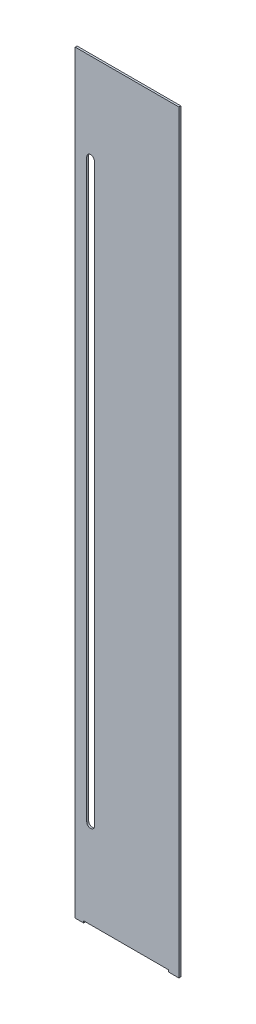
SolidWorks part; units mm, degrees
ref_plane "Front Plane" through (0, 0, 0) normal (0, 0, 1) x (1, 0, 0)
ref_plane "Top Plane" through (0, 0, 0) normal (0, 1, 0) x (1, 0, 0)
ref_plane "Right Plane" through (0, 0, 0) normal (1, 0, 0) x (0, 0, -1)
sketch "Sketch1" plane through (0, 0, 0) normal (0, 0, 1) x (1, 0, 0)
  line L1 (-135, 982.5) -> (135, 982.5)
  line L2 (-135, 982.5) -> (-135, -982.5)
  line L3 (-135, -982.5) -> (135, -982.5)
  line L4 (135, 982.5) -> (135, -982.5)
  line L5 (-135, 982.5) -> (135, -982.5) construction
  line L6 (-135, -982.5) -> (135, 982.5) construction
  point P0 (0, 0)
  dimension "D1" = 270
  dimension "D2" = 1965
extrude "Main plate extrude" add sketch "Sketch1" along normal blind 5
sketch "Sketch2" plane through (0, 0, 5) normal (0, 0, 1) x (1, 0, 0)
  line L0 (-135, -982.5) -> (135, -982.5) construction
  line L1 (-113, -982.5) -> (108, -982.5)
  line L2 (-113, -982.5) -> (-113, -977.5)
  line L3 (-113, -977.5) -> (108, -977.5)
  line L4 (108, -982.5) -> (108, -977.5)
  line L5 (-135, 982.5) -> (-135, -982.5) construction
  dimension "D1" = 5
  dimension "D2" = 221
  dimension "D3" = 22
extrude "Motor mount cut" cut sketch "Sketch2" against normal through all both and the other way through all
sketch "Sketch3" plane through (0, 0, 5) normal (0, 0, 1) x (1, 0, 0)
  line L0 (-95, 750) -> (-95, -750) construction
  line L1 (-85, 750) -> (-85, -750)
  line L2 (-105, 750) -> (-105, -750)
  line L3 (-135, 982.5) -> (-135, -982.5) construction
  arc A0 (-85, 750) -> (-105, 750) centre (-95, 750) ccw
  arc A1 (-105, -750) -> (-85, -750) centre (-95, -750) ccw
  point P2 (-95, 0)
  point P7 (0, 0)
  dimension "D1" = 1500
  dimension "D2" = 20
  dimension "D3" = 30
extrude "Output shaft slot" cut sketch "Sketch3" against normal through all both and the other way through all
